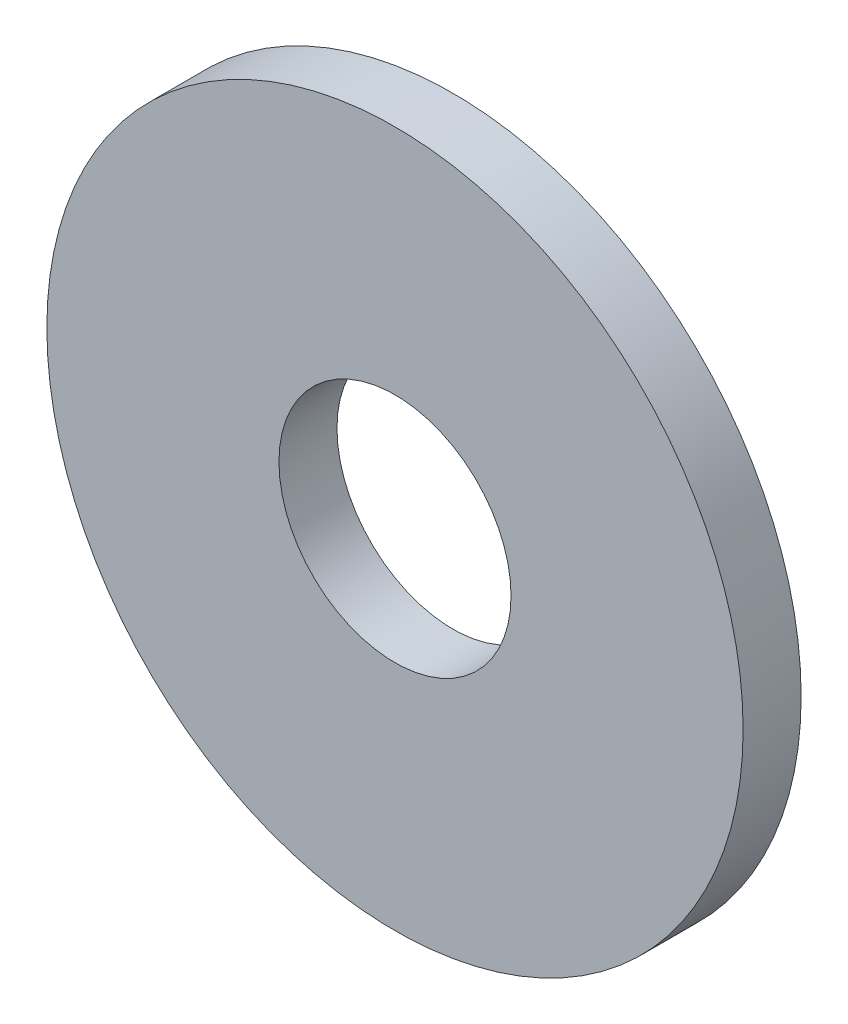
SolidWorks part; units mm, degrees
material "Alloy Steel"
ref_plane "Front Plane" through (0, 0, 0) normal (0, 0, 1) x (1, 0, 0)
ref_plane "Top Plane" through (0, 0, 0) normal (0, 1, 0) x (1, 0, 0)
ref_plane "Right Plane" through (0, 0, 0) normal (1, 0, 0) x (0, 0, -1)
sketch "Sketch1" plane through (0, 0, 0) normal (0, 0, 1) x (1, 0, 0)
  circle A0 centre (0, 0) radius 6
extrude "steel_washer" add sketch "Sketch1" along normal blind 1
sketch "Sketch2" plane through (0, 0, 1) normal (0, 0, 1) x (1, 0, 0)
  circle A0 centre (0, 0) radius 2
extrude "Cut-Extrude1" cut sketch "Sketch2" against normal through all
